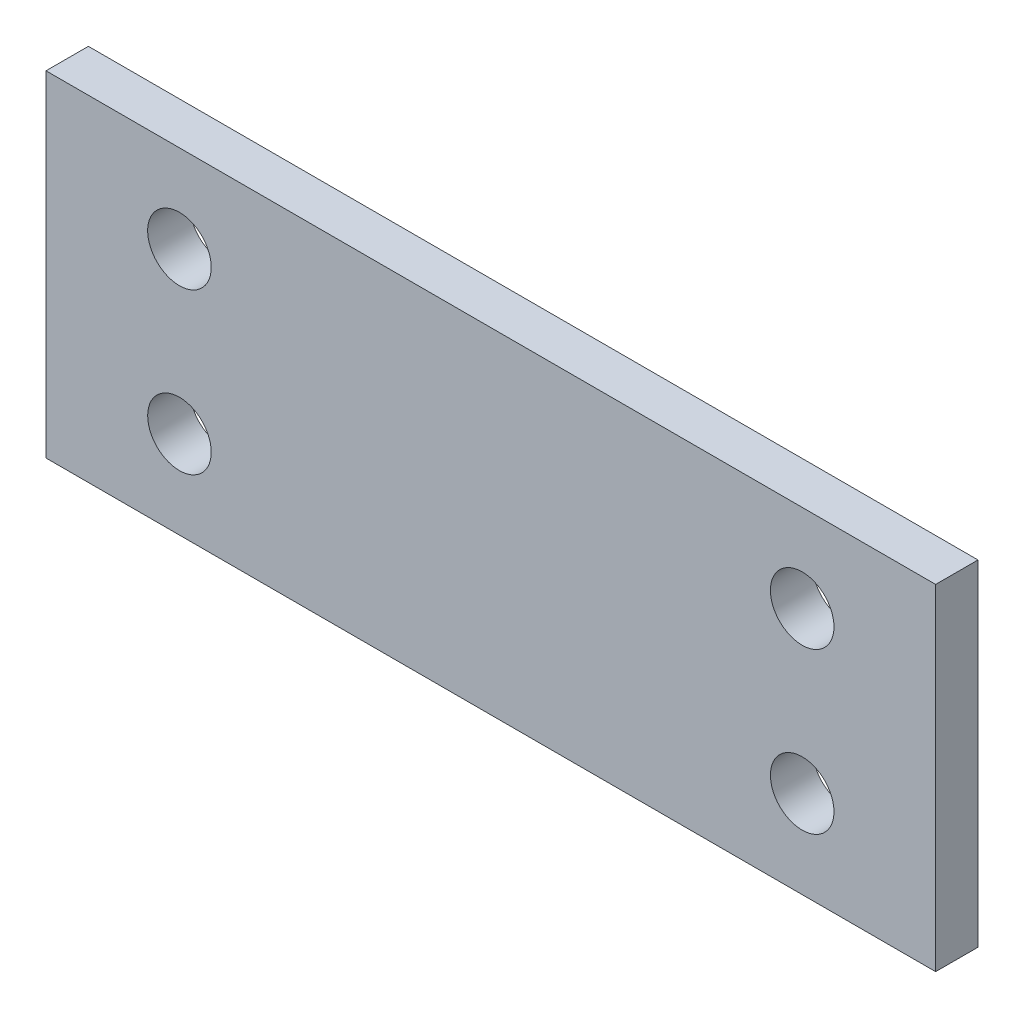
SolidWorks part; units mm, degrees
ref_plane "Alzado" through (0, 0, 0) normal (0, 0, 1) x (1, 0, 0)
ref_plane "Planta" through (0, 0, 0) normal (0, 1, 0) x (1, 0, 0)
ref_plane "Vista lateral" through (0, 0, 0) normal (1, 0, 0) x (0, 0, -1)
sketch "Croquis1" plane through (0, 0, 0) normal (0, 0, 1) x (1, 0, 0)
  line L0 (-100, 25.4) -> (100, 25.4)
  line L1 (-100, 25.4) -> (-100, -50)
  line L2 (-100, -50) -> (100, -50)
  line L3 (100, -50) -> (100, 25.4)
  line L4 (0, -50) -> (0, 25.4) construction
extrude "Saliente-Extruir1" add sketch "Croquis1" along normal blind 9.525
sketch "Croquis2" plane through (0, 0, 9.525) normal (0, 0, 1) x (1, 0, 0)
  line L0 (-100, -12.3) -> (-70, -12.3) construction
  line L1 (-100, 25.4) -> (-100, -50) construction
  line L2 (-70, -12.3) -> (-70, 5.7) construction
  line L3 (0, 25.4) -> (0, -50) construction
  line L4 (100, 25.4) -> (-100, 25.4) construction
  line L5 (-100, -50) -> (100, -50) construction
  line L6 (70, -12.3) -> (70, 5.7) construction
  circle A0 centre (-70, 5.7) radius 7.1438
  circle A1 centre (-70, -30.3) radius 7.1438
  circle A2 centre (70, -30.3) radius 7.1438
  circle A3 centre (70, 5.7) radius 7.1438
  dimension "D3" = 14.2875
  dimension "D1" = 30
  dimension "D2" = 18
extrude "Cortar-Extruir1" cut sketch "Croquis2" against normal blind 10
